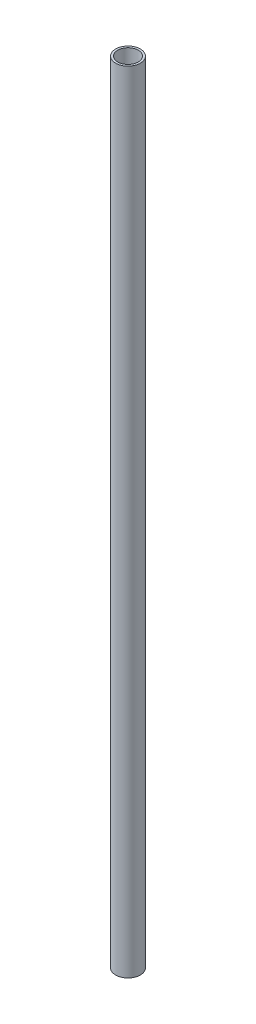
SolidWorks part; units mm, degrees
material "AISI 4130 Steel, annealed at 865C"
ref_plane "Front Plane" through (0, 0, 0) normal (0, 0, 1) x (1, 0, 0)
ref_plane "Top Plane" through (0, 0, 0) normal (0, 1, 0) x (1, 0, 0)
ref_plane "Right Plane" through (0, 0, 0) normal (1, 0, 0) x (0, 0, -1)
sketch "Sketch1" plane through (0, 0, 0) normal (0, 1, 0) x (1, 0, 0)
  circle A0 centre (0, 0) radius 5.2832
  circle A1 centre (0, 0) radius 6.35
  dimension "D1" = 1.0668
  dimension "D2" = 12.7
extrude "Boss-Extrude1" add sketch "Sketch1" along normal blind 406.4
